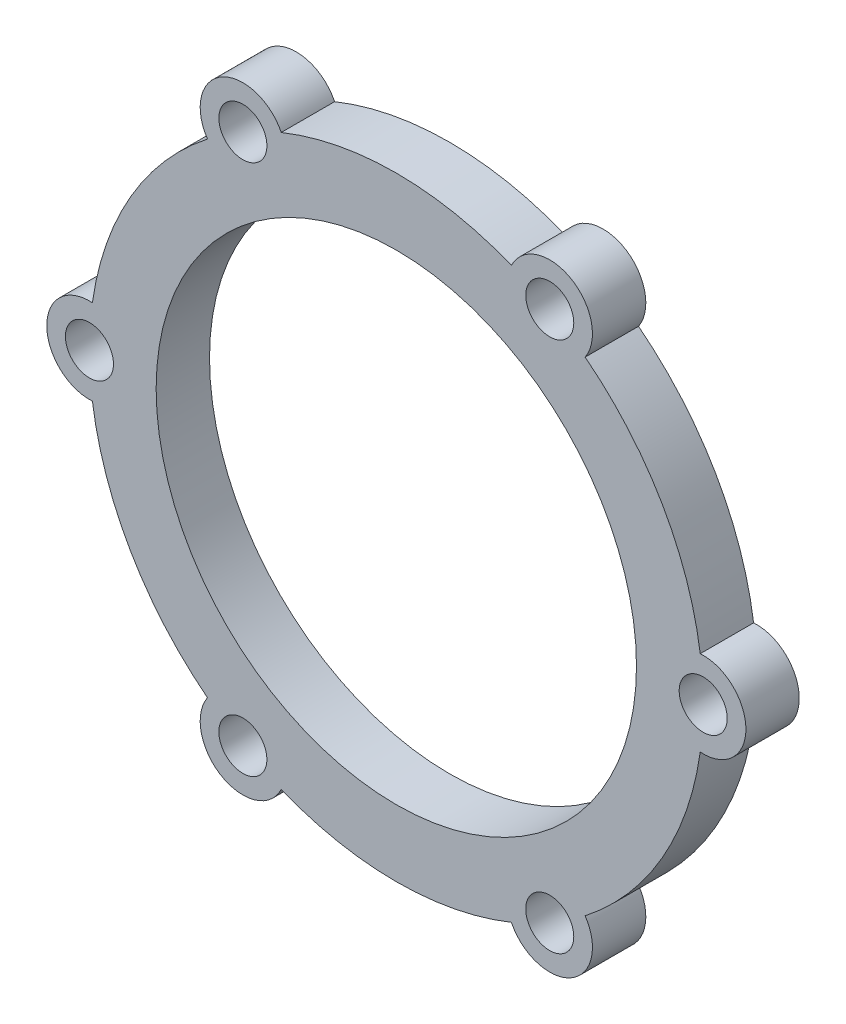
SolidWorks part; units mm, degrees
ref_plane "Front Plane" through (0, 0, 0) normal (0, 0, 1) x (1, 0, 0)
ref_plane "Top Plane" through (0, 0, 0) normal (0, 1, 0) x (1, 0, 0)
ref_plane "Right Plane" through (0, 0, 0) normal (1, 0, 0) x (0, 0, -1)
sketch "Sketch1" plane through (0, 0, 0) normal (0, 0, 1) x (1, 0, 0)
  line L0 (0, 0) -> (28.75, 49.7965) construction
  line L1 (0, 0) -> (57.5, 0) construction
  circle A0 centre (0, 0) radius 57.5
  circle A1 centre (0, 0) radius 45
  circle A2 centre (28.75, 49.7965) radius 4.5
  circle A3 centre (28.75, 49.7965) radius 8
  circle A4 centre (57.5, 0) radius 4.5
  circle A5 centre (57.5, 0) radius 8
  circle A6 centre (28.75, -49.7965) radius 4.5
  circle A7 centre (28.75, -49.7965) radius 8
  circle A8 centre (-28.75, -49.7965) radius 4.5
  circle A9 centre (-28.75, -49.7965) radius 8
  circle A10 centre (-57.5, 0) radius 4.5
  circle A11 centre (-57.5, 0) radius 8
  circle A12 centre (-28.75, 49.7965) radius 4.5
  circle A13 centre (-28.75, 49.7965) radius 8
  point P25 (0, 0)
  dimension "D1" = 115
  dimension "D2" = 90
  dimension "D4" = 9
  dimension "D5" = 16
  dimension "D3" = 60
  dimension "D6" = 6
extrude "Boss-Extrude1" add sketch "Sketch1" along normal blind 10 contours A13 A0 A11 A9 A7 A5 A3 A1 | A0 A13 A12 | A0 A13 A12 | A0 A3 A2 | A0 A3 A2 | A0 A5 A4 | A0 A5 A4 | A0 A7 A6 | A0 A7 A6 | A0 A9 A8 | A0 A9 A8 | A0 A11 A10 | A0 A11 A10
